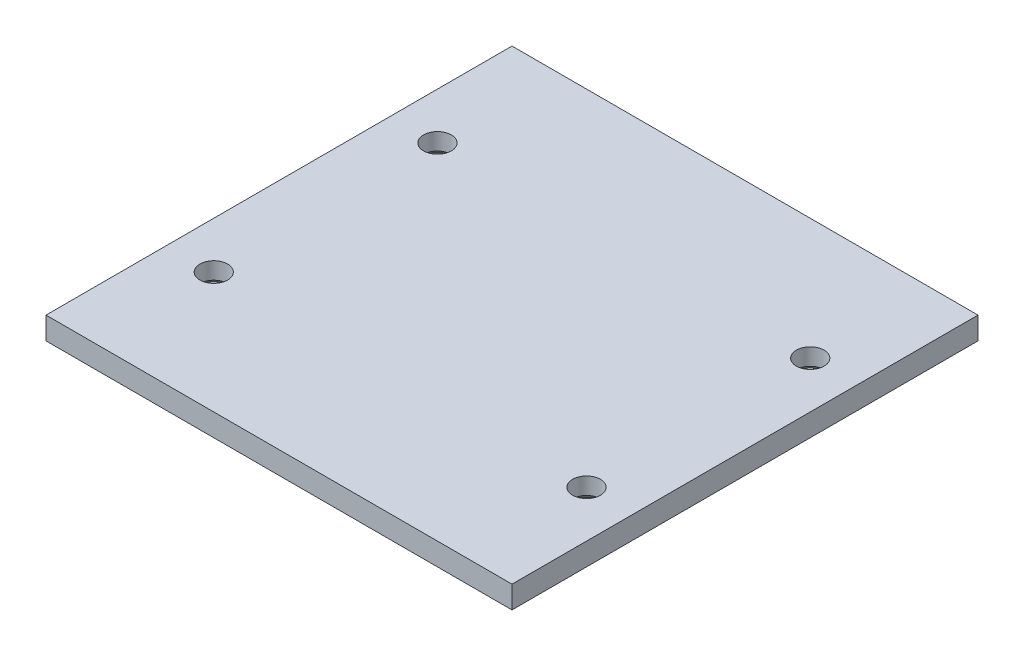
SolidWorks part; units mm, degrees
ref_plane "Front Plane" through (0, 0, 0) normal (0, 0, 1) x (1, 0, 0)
ref_plane "Top Plane" through (0, 0, 0) normal (0, 1, 0) x (1, 0, 0)
ref_plane "Right Plane" through (0, 0, 0) normal (1, 0, 0) x (0, 0, -1)
sketch "Sketch1" plane through (0, 0, 0) normal (0, 1, 0) x (1, 0, 0)
  line L0 (-62.5, 0) -> (62.5, 0) construction
  line L1 (-62.5, 62.5) -> (62.5, 62.5)
  line L2 (-62.5, 62.5) -> (-62.5, -62.5)
  line L3 (-62.5, -62.5) -> (62.5, -62.5)
  line L4 (62.5, 62.5) -> (62.5, -62.5)
  line L5 (0, 62.5) -> (0, -62.5) construction
  circle A1 centre (50, 30) radius 3.7244
  circle A4 centre (-50, 30) radius 3.7244
  circle A5 centre (-50, -30) radius 3.7244
  circle A6 centre (50, -30) radius 3.7244
  dimension "D1" = 125
  dimension "D2" = 125
  dimension "D3" = 62.5
  dimension "D4" = 62.5
  dimension "D5" = 12.5
  dimension "D6" = 32.5
  dimension "D7" = 2
  dimension "D8" = 2
extrude "Boss-Extrude2" add sketch "Sketch1" along normal blind 6
sketch "Sketch3" plane through (0, 0, -62.5) normal (0, 0, -1) x (-1, 0, 0)
  line L0 (-62.5, 0) -> (62.5, 0) construction
  circle A0 centre (0.7384, 3) radius 2
  dimension "D1" = 3
extrude "Cut-Extrude1" cut sketch "Sketch3" against normal blind 5 contours A0
hole_wizard "CSK for M5 Flat Head Machine Screw1" positions "3DSketch1" profile "Sketch4" countersink size "M5" standard "ANSI Metric"
sketch3d "3DSketch1"
  line L0 (50, 6, -30) -> (50, 0, -30) construction
  circle A0 centre (50, 0, -30) radius 3.7244 construction
  point P0 (51.1361, 0, -33.5469)
  point P4 (50, 3.7244, -30)
  point P5 (50, 0, -30)
sketch "Sketch4" plane through (50, 0, -30) normal (1, 0, 0) x (0, 0, -1)
  line L0 (0, 0) -> (0, 7.7425)
  line L1 (0, 7.7425) -> (2.9, 6)
  line L2 (2.9, 6) -> (2.9, 2.3)
  line L3 (2.9, 2.3) -> (5.2, 0)
  line L5 (5.2, 0) -> (0, 0)
  line L6 (-2.9, 2.3) -> (-5.2, 0) construction
  line L10 (0, 7.7425) -> (-2.9, 6) construction
  line L11 (0, -6.35) -> (0, 107.95) construction
  dimension "Hole Dia." = 5.8
  dimension "Hole Depth" = 6
  dimension "Near C'Sink Dia." = 10.4
  dimension "Near C'Sink Angle" = 90
  dimension "Drill Angle" = 118
hole_wizard "CSK for M5 Flat Head Machine Screw3" positions "3DSketch2" profile "Sketch5" countersink size "M5" standard "ANSI Metric"
sketch3d "3DSketch2"
  line L0 (-50, 6, -30) -> (-50, 0, -30) construction
  point P0 (-50, 0, -30)
sketch "Sketch5" plane through (-50, 0, -30) normal (1, 0, 0) x (0, 0, -1)
  line L0 (0, 0) -> (0, 7.7425)
  line L1 (0, 7.7425) -> (2.9, 6)
  line L2 (2.9, 6) -> (2.9, 2.3)
  line L3 (2.9, 2.3) -> (5.2, 0)
  line L5 (5.2, 0) -> (0, 0)
  line L6 (-2.9, 2.3) -> (-5.2, 0) construction
  line L10 (0, 7.7425) -> (-2.9, 6) construction
  line L11 (0, -6.35) -> (0, 107.95) construction
  dimension "Hole Dia." = 5.8
  dimension "Hole Depth" = 6
  dimension "Near C'Sink Dia." = 10.4
  dimension "Near C'Sink Angle" = 90
  dimension "Drill Angle" = 118
hole_wizard "CSK for M5 Flat Head Machine Screw4" positions "3DSketch3" profile "Sketch6" countersink size "M5" standard "ANSI Metric"
sketch3d "3DSketch3"
  line L0 (-50, 6, 30) -> (-50, 0, 30) construction
  point P0 (-50.0541, 0.8445, 26.2714)
  point P1 (-50, 0, 30)
sketch "Sketch6" plane through (-50, 0, 30) normal (1, 0, 0) x (0, 0, -1)
  line L0 (0, 0) -> (0, 7.7425)
  line L1 (0, 7.7425) -> (2.9, 6)
  line L2 (2.9, 6) -> (2.9, 2.3)
  line L3 (2.9, 2.3) -> (5.2, 0)
  line L5 (5.2, 0) -> (0, 0)
  line L6 (-2.9, 2.3) -> (-5.2, 0) construction
  line L10 (0, 7.7425) -> (-2.9, 6) construction
  line L11 (0, -6.35) -> (0, 107.95) construction
  dimension "Hole Dia." = 5.8
  dimension "Hole Depth" = 6
  dimension "Near C'Sink Dia." = 10.4
  dimension "Near C'Sink Angle" = 90
  dimension "Drill Angle" = 118
hole_wizard "CSK for M5 Flat Head Machine Screw5" positions "3DSketch5" profile "Sketch8" countersink size "M5" standard "ANSI Metric"
sketch3d "3DSketch5"
  line L0 (50, 6, 30) -> (50, 0, 30) construction
  point P0 (47.2817, 3.3325, 27.4539)
  point P1 (50, 0, 30)
sketch "Sketch8" plane through (50, 0, 30) normal (1, 0, 0) x (0, 0, -1)
  line L0 (0, 0) -> (0, 7.7425)
  line L1 (0, 7.7425) -> (2.9, 6)
  line L2 (2.9, 6) -> (2.9, 2.3)
  line L3 (2.9, 2.3) -> (5.2, 0)
  line L5 (5.2, 0) -> (0, 0)
  line L6 (-2.9, 2.3) -> (-5.2, 0) construction
  line L10 (0, 7.7425) -> (-2.9, 6) construction
  line L11 (0, -6.35) -> (0, 107.95) construction
  dimension "Hole Dia." = 5.8
  dimension "Hole Depth" = 6
  dimension "Near C'Sink Dia." = 10.4
  dimension "Near C'Sink Angle" = 90
  dimension "Drill Angle" = 118
